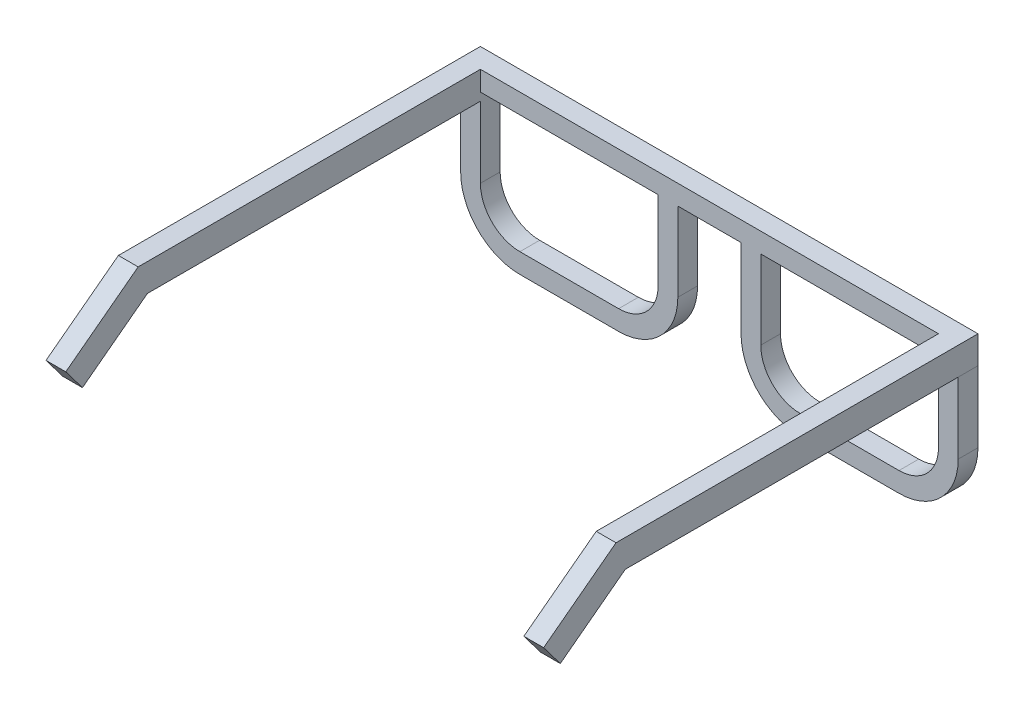
SolidWorks part; units mm, degrees
ref_plane "正面" through (0, 0, 0) normal (0, 0, 1) x (1, 0, 0)
ref_plane "平面" through (0, 0, 0) normal (0, 1, 0) x (1, 0, 0)
ref_plane "右側面" through (0, 0, 0) normal (1, 0, 0) x (0, 0, -1)
sketch "ｽｹｯﾁ1" plane through (0, 0, 0) normal (0, 0, 1) x (1, 0, 0)
  line L1 (-63, 21.5334) -> (-8, 21.5334)
  line L2 (-63, 21.5334) -> (-63, -18.4666)
  line L3 (-63, -18.4666) -> (-8, -18.4666)
  line L4 (-8, 21.5334) -> (-8, -18.4666)
  line L5 (8, 21.5334) -> (63, 21.5334)
  line L6 (8, 21.5334) -> (8, -18.4666)
  line L7 (8, -18.4666) -> (63, -18.4666)
  line L8 (63, 21.5334) -> (63, -18.4666)
  line L9 (-58, 16.5334) -> (-13, 16.5334)
  line L10 (-58, 16.5334) -> (-58, -13.4666)
  line L11 (-58, -13.4666) -> (-13, -13.4666)
  line L12 (-13, 16.5334) -> (-13, -13.4666)
  line L13 (13, 16.5334) -> (58, 16.5334)
  line L14 (13, 16.5334) -> (13, -13.4666)
  line L15 (13, -13.4666) -> (58, -13.4666)
  line L16 (58, 16.5334) -> (58, -13.4666)
  line L17 (-8, 21.5334) -> (8, 21.5334)
  line L18 (-8, 21.5334) -> (-8, 16.5334)
  line L19 (-8, 16.5334) -> (8, 16.5334)
  line L20 (8, 21.5334) -> (8, 16.5334)
  line L21 (0, -55) -> (0, 55) construction
  point P18 (81.3051, -15.5123)
  point P19 (77.7391, -16.9387)
  point P20 (-3.5666, -12.6297)
  point P21 (37.7994, -11.9462)
  point P22 (38.5126, 15.5123)
  point P23 (-2.8534, 19.7618)
  point P24 (0, 0)
  dimension "D1" = 126
  dimension "D2" = 40
  dimension "D3" = 40
  dimension "D4" = 55
  dimension "D5" = 55
  dimension "D6" = 5
  dimension "D7" = 5
  dimension "D8" = 5
  dimension "D9" = 5
  dimension "D10" = 5
  dimension "D11" = 5
  dimension "D12" = 5
  dimension "D13" = 5
  dimension "D14" = 5
  dimension "D15" = 63
extrude "ﾎﾞｽ - 押し出し1" add sketch "ｽｹｯﾁ1" along normal blind 5 contours L8 L5 L6 L7 L13 L16 L15 L14 | L4 L19 L6 L17 | L4 L1 L2 L3 L9 L12 L11 L10
fillet "ﾌｨﾚｯﾄ1" radius 10 4 edges at (58, -13.4666, 2.5) (13, -13.4666, 2.5) (-13, -13.4666, 2.5) (-58, -13.4666, 2.5)
fillet "ﾌｨﾚｯﾄ2" radius 15 4 edges at (63, -18.4666, 2.5) (8, -18.4666, 2.5) (-8, -18.4666, 2.5) (-63, -18.4666, 2.5)
sketch "ｽｹｯﾁ2" plane through (-63, 0, 0) normal (-1, 0, 0) x (0, 0, 1)
  line L0 (91.6712, 21.5334) -> (110, 7.6845)
  line L1 (0, 21.5334) -> (91.6712, 21.5334)
  line L2 (0, 21.5334) -> (0, 14.5334)
  line L3 (0, 14.5334) -> (91.6712, 14.5334)
  line L4 (91.6712, 21.5334) -> (91.6712, 14.5334)
  line L5 (91.6712, 21.5334) -> (87.4512, 15.9484)
  line L6 (110, 7.6845) -> (105.7801, 2.0995)
  line L7 (87.4512, 15.9484) -> (105.7801, 2.0995)
  point P5 (96.6157, 9.024)
  point P7 (110, 7.6845)
  line M8 (0, 21.5334) -> (0, -3.4666)
  line M10 (5, -3.4666) -> (5, 21.5334)
  line M11 (5, 21.5334) -> (0, 21.5334)
  dimension "D1" = 7
  dimension "D2" = 7
  dimension "D3" = 110
extrude "ﾎﾞｽ - 押し出し2" add sketch "ｽｹｯﾁ2" against normal blind 5 and the other way blind 0.01 contours L3 M8 M10 M11 | L7 L5 L1 L3 M10 | L5 L7 L3 L4 | L3 L7 L6 L0 L4
mirror "ﾐﾗｰ1" about plane through (0, 0, 0) normal (1, 0, 0) of "ﾎﾞｽ - 押し出し1", "ﾎﾞｽ - 押し出し2"
fillet "ﾌｨﾚｯﾄ3" radius 15 4 edges at (63, -18.4666, 2.5) (8, -18.4666, 2.5) (-8, -18.4666, 2.5) (-63, -18.4666, 2.5)
